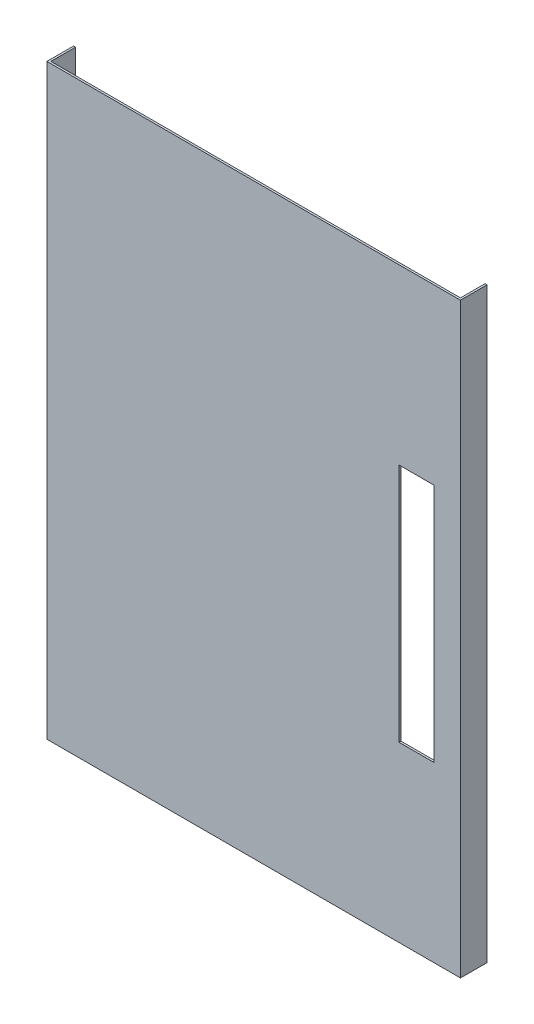
SolidWorks part; units mm, degrees
ref_plane "Front Plane" through (0, 0, 0) normal (0, 0, 1) x (1, 0, 0)
ref_plane "Top Plane" through (0, 0, 0) normal (0, 1, 0) x (1, 0, 0)
ref_plane "Right Plane" through (0, 0, 0) normal (1, 0, 0) x (0, 0, -1)
other "Configuration Table"
sketch "Sketch1" plane through (0, 0, 0) normal (0, 1, 0) x (1, 0, 0)
  line L0 (30, -40) -> (30, -20)
  line L1 (30, -20) -> (31.5, -20)
  line L2 (31.5, -20) -> (31.5, -38.5)
  line L3 (31.5, -38.5) -> (338.5, -38.5)
  line L4 (338.5, -38.5) -> (338.5, -20)
  line L5 (338.5, -20) -> (340, -20)
  line L6 (340, -20) -> (340, -40)
  line L7 (340, -40) -> (30, -40)
extrude "PRESS_kova_kapagi_kapak_1" add sketch "Sketch1" along normal blind 440 from offset 1340 separate body
sketch "Sketch2" plane through (0, 0, 0) normal (0, 0, 1) x (1, 0, 0)
  line L1 (294, 1470) -> (320, 1470)
  line L2 (294, 1470) -> (294, 1650)
  line L3 (294, 1650) -> (320, 1650)
  line L4 (320, 1470) -> (320, 1650)
extrude "PRESS_kova_kapagi_kapak_2" cut sketch "Sketch2" along normal blind 14 from offset 27
